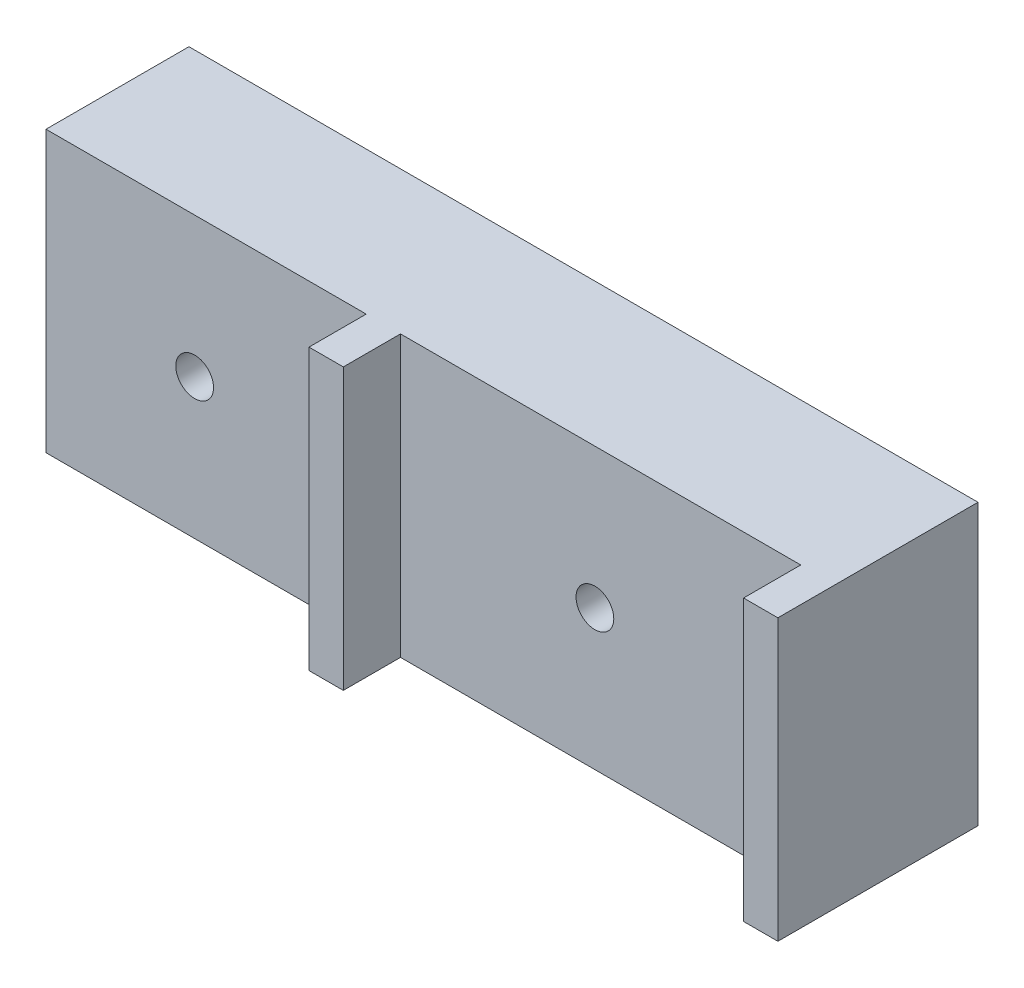
SolidWorks part; units mm, degrees
ref_plane "Plane Front" through (0, 0, 0) normal (0, 0, 1) x (1, 0, 0)
ref_plane "Plane Top" through (0, 0, 0) normal (0, 1, 0) x (1, 0, 0)
ref_plane "Plane Right" through (0, 0, 0) normal (1, 0, 0) x (0, 0, -1)
sketch "Sketch2" plane through (0, 0, 0) normal (0, 0, 1) x (1, 0, 0)
  line L1 (-34.5, -12.25) -> (34.5, -12.25)
  line L2 (-34.5, -12.25) -> (-34.5, 12.25)
  line L3 (-34.5, 12.25) -> (34.5, 12.25)
  line L4 (34.5, -12.25) -> (34.5, 12.25)
  line L5 (-34.5, -12.25) -> (34.5, 12.25) construction
  line L6 (-34.5, 12.25) -> (34.5, -12.25) construction
  point P0 (0, 0)
  dimension "D1" = 24.5
  dimension "D2" = 69
extrude "Extrude1" add sketch "Sketch2" along normal blind 12.5
sketch "Sketch3" plane through (0, 0, 12.5) normal (0, 0, 1) x (1, 0, 0)
  line L0 (6.875, 0) -> (-6.875, 0) construction
  line L1 (-34.5, 12.25) -> (-34.5, -12.25) construction
  circle A0 centre (-21.5, 0) radius 1.65
  circle A1 centre (13.5, 0) radius 1.65
  dimension "D1" = 3.3
  dimension "D2" = 35
  dimension "D3" = 13
extrude "Extrude2" cut sketch "Sketch3" against normal through all
sketch "Sketch4" plane through (0, 0, 12.5) normal (0, 0, 1) x (1, 0, 0)
  line L0 (34.5, 12.25) -> (-34.5, 12.25) construction
  line L1 (34.5, 12.25) -> (31.5, 12.25)
  line L2 (34.5, 12.25) -> (34.5, -12.25)
  line L3 (34.5, -12.25) -> (31.5, -12.25)
  line L4 (31.5, 12.25) -> (31.5, -12.25)
  line L5 (-6.5, 12.25) -> (-3.5, 12.25)
  line L6 (-6.5, 12.25) -> (-6.5, -12.25)
  line L7 (-6.5, -12.25) -> (-3.5, -12.25)
  line L8 (-3.5, 12.25) -> (-3.5, -12.25)
  line L9 (-34.5, -12.25) -> (34.5, -12.25) construction
  dimension "D1" = 3
  dimension "D2" = 3
  dimension "D3" = 35
extrude "Extrude3" add sketch "Sketch4" along normal blind 5
